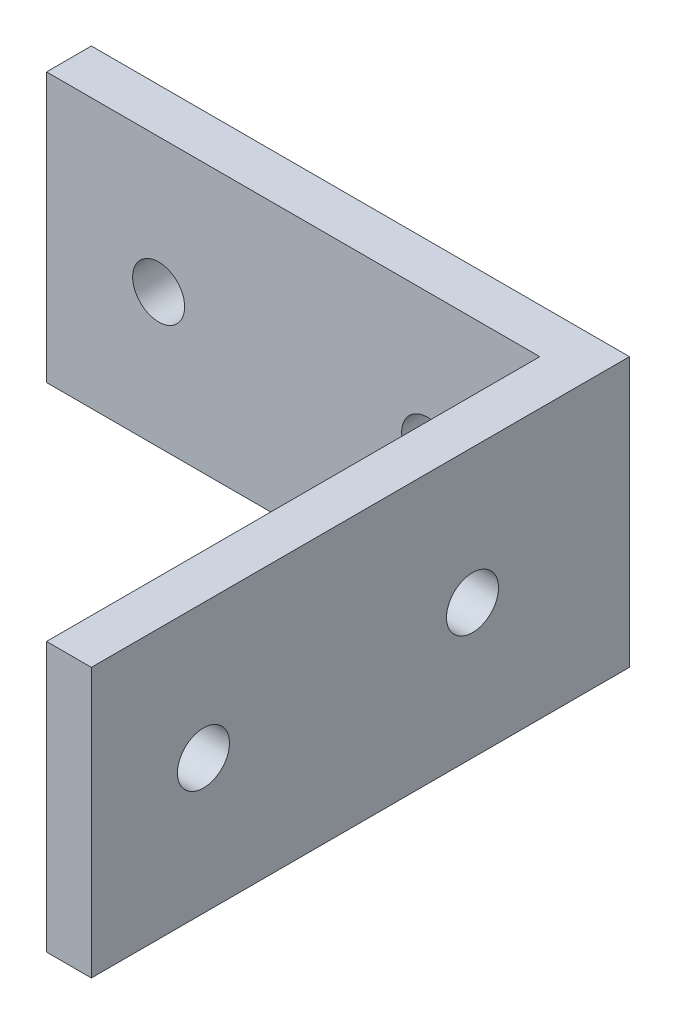
SolidWorks part; units mm, degrees
ref_plane "Front Plane" through (0, 0, 0) normal (0, 0, 1) x (1, 0, 0)
ref_plane "Top Plane" through (0, 0, 0) normal (0, 1, 0) x (1, 0, 0)
ref_plane "Right Plane" through (0, 0, 0) normal (1, 0, 0) x (0, 0, -1)
sketch "Sketch1" plane through (0, 0, 0) normal (0, 1, 0) x (1, 0, 0)
  line L1 (-38.1, 38.1) -> (38.1, 38.1)
  line L2 (-38.1, 38.1) -> (-38.1, -38.1)
  line L3 (-38.1, -38.1) -> (38.1, -38.1)
  line L4 (38.1, 38.1) -> (38.1, -38.1)
  line L5 (-38.1, 38.1) -> (38.1, -38.1) construction
  line L6 (-38.1, -38.1) -> (38.1, 38.1) construction
  point P0 (0, 0)
  dimension "D1" = 76.2
  dimension "D2" = 76.2
extrude "Boss-Extrude1" add sketch "Sketch1" along normal blind 38.1
sketch "Sketch2" plane through (0, 38.1, 0) normal (0, 1, 0) x (1, 0, 0)
  line L0 (38.1, -38.1) -> (38.1, 38.1) construction
  line L1 (-38.1, 38.1) -> (38.1, 38.1)
  line L2 (-38.1, 38.1) -> (-38.1, 31.75)
  line L4 (38.1, 38.1) -> (38.1, 31.75)
  line L5 (-38.1, 31.75) -> (31.75, 31.75)
  line L7 (31.75, 31.75) -> (31.75, -38.1)
  line L8 (31.75, -38.1) -> (38.1, -38.1)
  line L9 (38.1, 31.75) -> (38.1, -38.1)
  dimension "D1" = 6.35
extrude "Cut-Extrude1" cut sketch "Sketch2" against normal through all flip side to cut
sketch "Sketch4" plane through (0, 0, -31.75) normal (0, 0, 1) x (1, 0, 0)
  line L0 (-38.1, 19.05) -> (31.75, 19.05) construction
  line L1 (-38.1, 0) -> (-38.1, 38.1) construction
  line L2 (31.75, 0) -> (31.75, 38.1) construction
  line L3 (-22.225, 19.05) -> (-38.1, 19.05)
  line L4 (15.875, 19.05) -> (31.75, 19.05)
  circle A0 centre (-22.225, 19.05) radius 3.683
  circle A1 centre (15.875, 19.05) radius 3.683
  dimension "D2" = 7.366
  dimension "D1" = 38.1
sketch "Sketch5" plane through (31.75, 0, 0) normal (-1, 0, 0) x (0, 0, 1)
  line L0 (-31.75, 19.05) -> (38.1, 19.05) construction
  line L1 (38.1, 0) -> (38.1, 38.1) construction
  line L2 (-15.875, 19.05) -> (-31.75, 19.05)
  line L3 (22.225, 19.05) -> (38.1, 19.05)
  circle A0 centre (-15.875, 19.05) radius 3.683
  circle A1 centre (22.225, 19.05) radius 3.683
  dimension "D1" = 7.366
  dimension "D2" = 38.1
extrude "Cut-Extrude2" cut sketch "Sketch4" against normal blind 38.1 contours L3 L0 A0 | L0 L3 A0 | A1 L0 L4 | L0 A1 L4
extrude "Cut-Extrude3" cut sketch "Sketch5" against normal blind 38.1 contours L2 L0 A0 | L0 L2 A0 | A1 L0 L3 | L0 A1 L3
